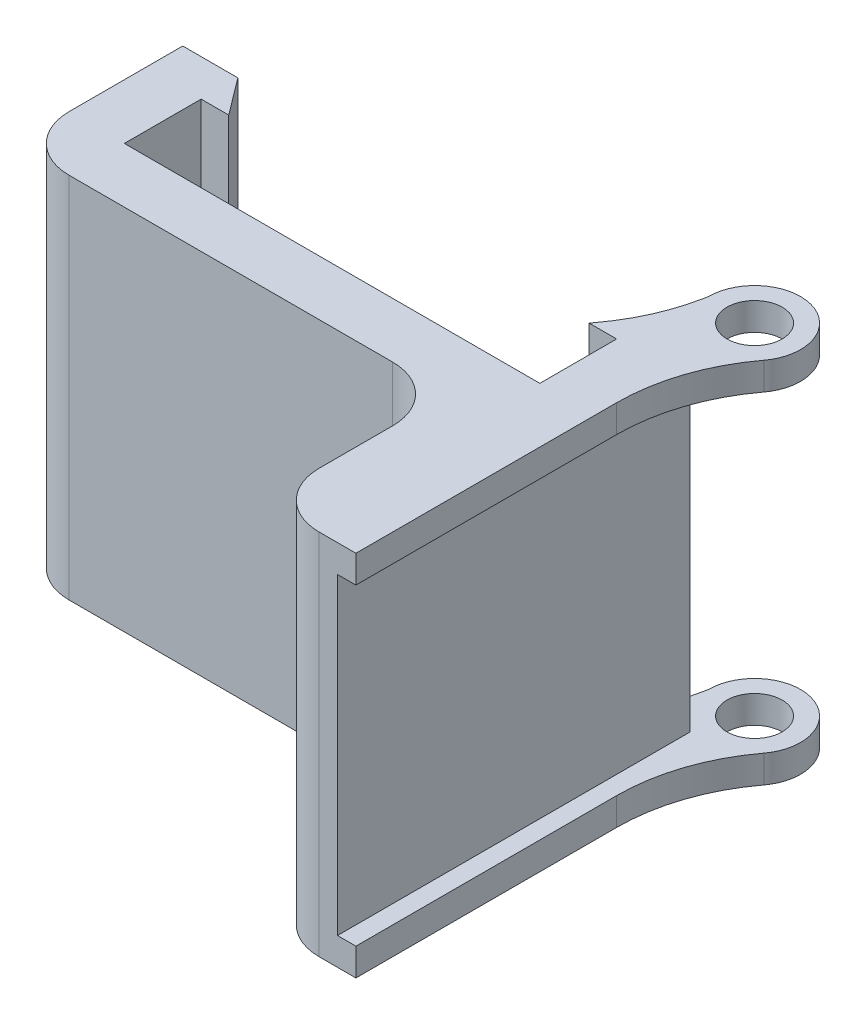
SolidWorks part; units mm, degrees
ref_plane "Front Plane" through (0, 0, 0) normal (0, 0, 1) x (1, 0, 0)
ref_plane "Top Plane" through (0, 0, 0) normal (0, 1, 0) x (1, 0, 0)
ref_plane "Right Plane" through (0, 0, 0) normal (1, 0, 0) x (0, 0, -1)
sketch "Sketch1" plane through (0, 0, 24.175) normal (0, 0, 1) x (1, 0, 0)
  line L0 (-14.295, 75.692) -> (14.295, 75.692)
  line L1 (-14.295, 55.692) -> (14.295, 55.692)
  line L2 (-14.295, 55.692) -> (-14.295, 75.692)
  line L3 (14.295, 55.692) -> (14.295, 75.692)
  line L4 (-10.795, 23.495) -> (-10.795, 95.5796) construction
  arc A0 (-3.0486, 76.9696) -> (-76.9008, 4.46) centre (0, 0) ccw construction
  arc A1 (76.9696, 3.0486) -> (4.46, 76.9008) centre (0, 0) ccw construction
  point P7 (14.4137, 75.6695)
  point P11 (-13.0182, 58.1499)
  point P12 (0, 0)
  dimension "D1" = 3.5
  dimension "D2" = 20
extrude "Boss-Extrude1" add sketch "Sketch1" along normal blind 3
sketch "Sketch2" plane through (0, 0, 24.175) normal (0, 0, -1) x (-1, 0, 0)
  line L0 (14.295, 55.692) -> (-14.295, 55.692) construction
  line L1 (-14.295, 75.692) -> (-11.295, 75.692)
  line L2 (-14.295, 75.692) -> (-14.295, 55.692)
  line L3 (-14.295, 55.692) -> (-11.295, 55.692)
  line L4 (-11.295, 75.692) -> (-11.295, 55.692)
  line L5 (-10.795, 23.495) -> (-10.795, 95.5796) construction
  line L6 (14.295, 75.692) -> (11.295, 75.692)
  line L7 (14.295, 75.692) -> (14.295, 55.692)
  line L8 (14.295, 55.692) -> (11.295, 55.692)
  line L9 (11.295, 75.692) -> (11.295, 55.692)
  line L10 (10.795, 23.495) -> (10.795, 95.5796) construction
  dimension "D1" = 3
  dimension "D2" = 3
extrude "Boss-Extrude2" add sketch "Sketch2" along normal offset from surface (6.175 mm away) 3
sketch "Sketch4" plane through (0, 75.692, 0) normal (0, 1, 0) x (1, 0, 0)
  line L0 (-11.295, -20) -> (-11.295, -18)
  line L1 (11.295, -18) -> (11.295, -20)
  line L2 (-11.295, -18) -> (-9.795, -20)
  line L3 (-9.795, -20) -> (-11.295, -20)
  line L4 (-11.295, -18) -> (-11.295, -24.175) construction
  line L5 (142.875, -21) -> (-142.875, -21) construction
  line L6 (11.295, -18) -> (11.295, -24.175) construction
  line L7 (11.295, -20) -> (9.795, -20)
  line L8 (9.795, -20) -> (11.295, -18)
  line L9 (10.9665, -21) -> (-10.9664, -21) construction
  dimension "D1" = 1.5
  dimension "D2" = 1
  dimension "D3" = 1.5
  dimension "D4" = 1
extrude "Boss-Extrude3" add sketch "Sketch4" against normal up to surface (20 mm away) up to face at (0, 55.692, 21.8375)
sketch "Sketch5" plane through (0, 0, 27.175) normal (0, 0, 1) x (1, 0, 0)
  line L0 (-14.295, 55.692) -> (14.295, 55.692) construction
  line L1 (14.295, 75.692) -> (9.295, 75.692)
  line L2 (14.295, 75.692) -> (14.295, 55.692)
  line L3 (14.295, 55.692) -> (9.295, 55.692)
  line L4 (9.295, 75.692) -> (9.295, 55.692)
  dimension "D1" = 5
extrude "Boss-Extrude4" add sketch "Sketch5" along normal blind 10
sketch "Sketch6" plane through (0, 55.692, 0) normal (0, -1, 0) x (1, 0, 0)
  line L0 (14.295, 18) -> (11.295, 18) construction
  line L1 (14.295, 18) -> (14.295, 15.5) construction
  line L2 (11.295, 18) -> (11.795, 15.5)
  line L3 (11.295, 18) -> (14.295, 18)
  arc A0 (11.795, 15.5) -> (14.295, 18) centre (14.295, 15.5) ccw
  dimension "D1" = 5
extrude "Boss-Extrude5" add sketch "Sketch6" against normal blind 1.5
sketch "Sketch7" plane through (0, 75.692, 0) normal (0, 1, 0) x (1, 0, 0)
  line L0 (11.295, -18) -> (11.795, -15.5)
  line L1 (11.295, -18) -> (14.295, -18)
  circle A0 centre (14.295, -15.5) radius 2.5 construction
  arc A1 (14.295, -18) -> (11.795, -15.5) centre (14.295, -15.5) ccw
extrude "Boss-Extrude6" add sketch "Sketch7" against normal blind 1.5
sketch "Sketch8" plane through (0, 75.692, 0) normal (0, 1, 0) x (1, 0, 0)
  circle A0 centre (14.295, -15.5) radius 1.5
  circle A1 centre (14.295, -15.5) radius 1 construction
  dimension "D1" = 0.5
extrude "Cut-Extrude1" cut sketch "Sketch8" against normal up to surface (20 mm away)
sketch "Sketch9" plane through (14.295, 0, 0) normal (1, 0, 0) x (0, 0, -1)
  line L0 (-37.175, 55.692) -> (-37.175, 75.692) construction
  line L1 (-37.175, 74.192) -> (-18, 74.192)
  line L2 (-37.175, 74.192) -> (-37.175, 57.192)
  line L3 (-37.175, 57.192) -> (-18, 57.192)
  line L4 (-18, 74.192) -> (-18, 57.192)
  point P7 (-18, 74.192)
  point P9 (0, 0)
  point P10 (0, 0)
extrude "Cut-Extrude2" cut sketch "Sketch9" against normal blind 1
fillet "Fillet1" radius 10 2 edges at (14.295, 56.442, 18) (14.295, 74.942, 18)
fillet "Fillet2" radius 10 2 edges at (11.295, 56.442, 18) (11.295, 74.942, 18)
fillet "Fillet3" radius 3 3 edges at (9.295, 65.692, 37.175) (9.295, 65.692, 27.175) (-14.295, 65.692, 27.175)
